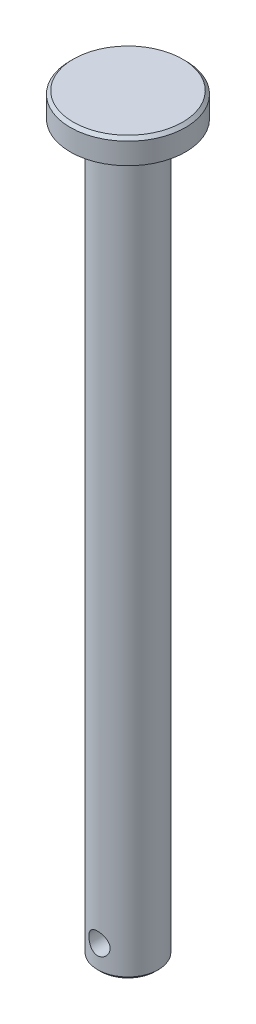
SolidWorks part; units mm, degrees
material "AISI 1020"
ref_plane "Plano frontal" through (0, 0, 0) normal (0, 0, 1) x (1, 0, 0)
ref_plane "Plano superior" through (0, 0, 0) normal (0, 1, 0) x (1, 0, 0)
ref_plane "Plano direito" through (0, 0, 0) normal (1, 0, 0) x (0, 0, -1)
sketch "Esboço1" plane through (0, 0, 0) normal (1, 0, 0) x (0, 0, -1)
  line L0 (0, 123.35) -> (0, -123.35) construction
  line L1 (0, 123.35) -> (18, 123.35)
  line L2 (19, 122.35) -> (19, 115.35)
  line L3 (19, 115.35) -> (10, 115.35)
  line L4 (10, 115.35) -> (10, -122.35)
  line L5 (9, -123.35) -> (0, -123.35)
  line L6 (18, 123.35) -> (19, 122.35)
  line L7 (10, -122.35) -> (9, -123.35)
  line L8 (0, -123.35) -> (0, 123.35)
  point P4 (19, 123.35)
  point P7 (10, -123.35)
  dimension "D2" = 20
  dimension "D3" = 38
  dimension "D4" = 8
  dimension "D5" = 246.7
revolve "Revolução1" add sketch "Esboço1" angle 360 about L0
sketch "Esboço2" plane through (0, 0, 0) normal (0, 0, 1) x (1, 0, 0)
  line L0 (0, -123.35) -> (0, -114.85) construction
  line L1 (-9, -123.35) -> (9, -123.35) construction
  circle A0 centre (0, -114.85) radius 3.5
  dimension "D1" = 7
  dimension "D2" = 8.5
extrude "Corte-extrusão1" cut sketch "Esboço2" against normal through all both and the other way through all
